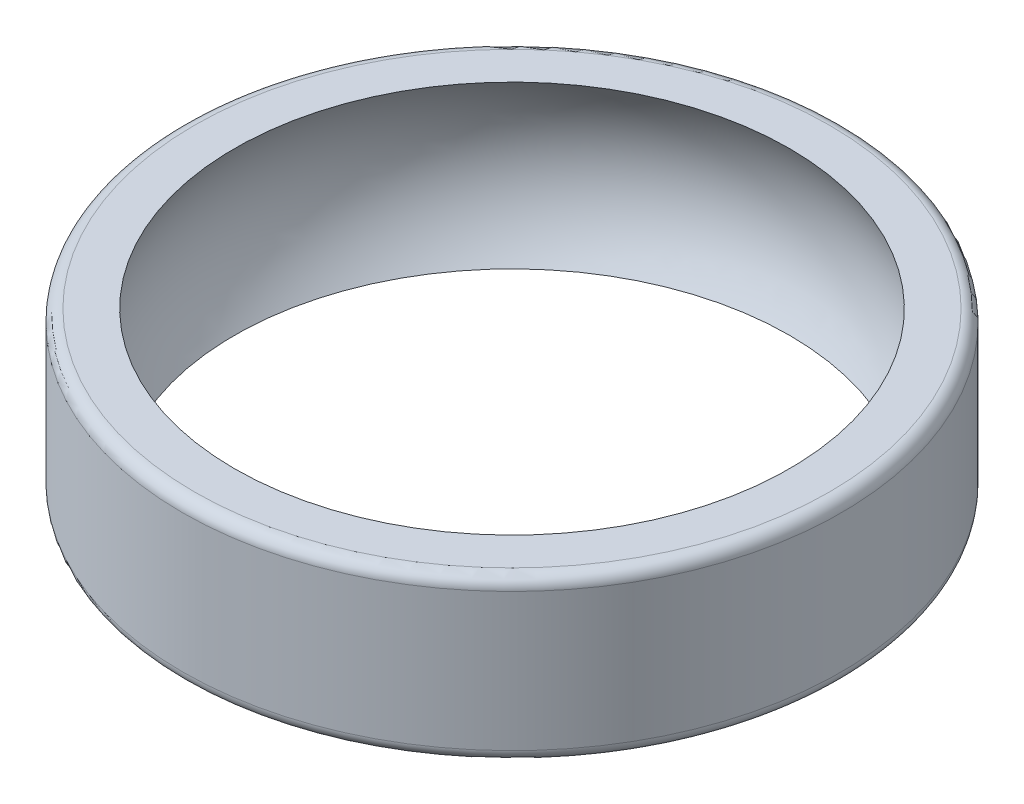
SolidWorks part; units mm, degrees
ref_plane "Front Plane" through (0, 0, 0) normal (0, 0, 1) x (1, 0, 0)
ref_plane "Top Plane" through (0, 0, 0) normal (0, 1, 0) x (1, 0, 0)
ref_plane "Right Plane" through (0, 0, 0) normal (1, 0, 0) x (0, 0, -1)
sketch "Sketch1" plane through (0, 0, 0) normal (0, 1, 0) x (1, 0, 0)
  circle A0 centre (0, 0) radius 46.3
  circle A1 centre (0, 0) radius 55
  dimension "D1" = 92.6
  dimension "D2" = 110
extrude "Boss-Extrude1" add sketch "Sketch1" along normal blind 27
fillet "Fillet1" radius 2 2 edges at (0, 0, 55) (0, 27, 55)
sketch "Sketch2" plane through (0, 0, 0) normal (0, 0, 1) x (1, 0, 0)
  line L0 (46.3, 27) -> (-46.3, 27) construction
  line L1 (46.3, 27) -> (-46.3, 27) construction
  line L2 (0, 0) -> (0, 27) construction
  line L3 (-46.3, 0) -> (0, 0) construction
  line L4 (-46.3, 27) -> (-46.3, 0)
  spline S0 degree 2 poles (-46.3, 27) (-55.6388, 13.5) (-46.3, 0) knots 0 0 0 1 1 1
  point P3 (0, 13.5)
revolve "Cut-Revolve1" cut sketch "Sketch2" angle 360 about L2
